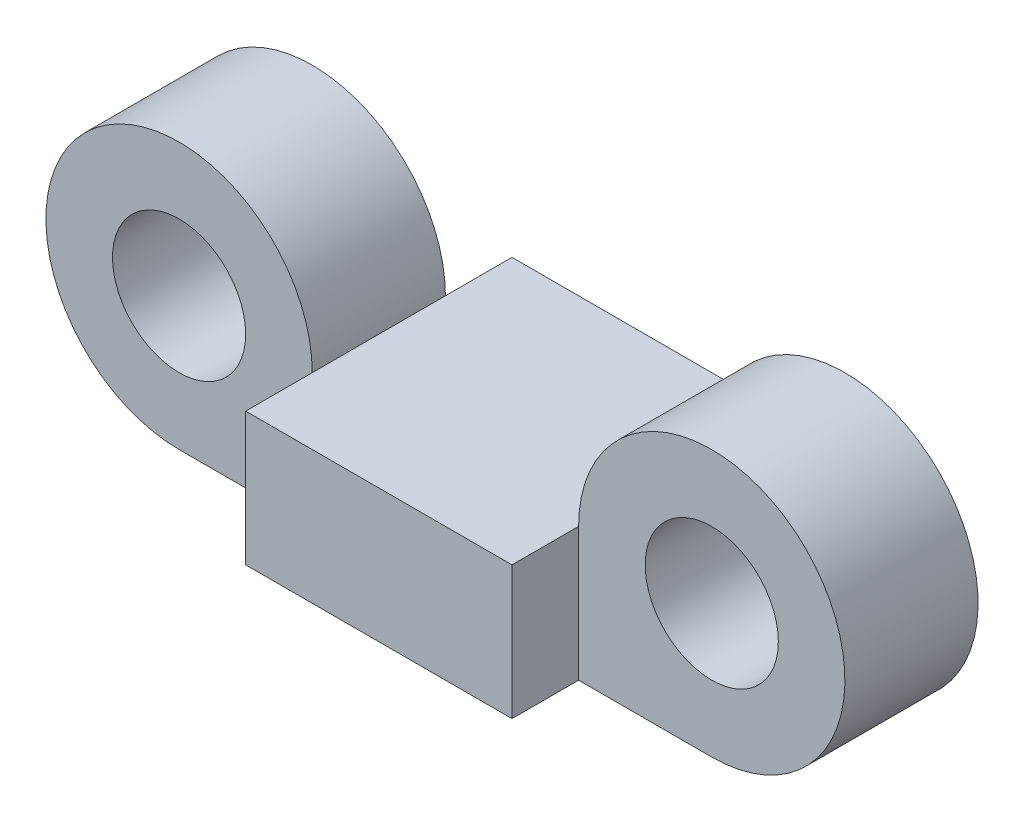
SolidWorks part; units mm, degrees
ref_plane "前视基准面" through (0, 0, 0) normal (0, 0, 1) x (1, 0, 0)
ref_plane "上视基准面" through (0, 0, 0) normal (0, 1, 0) x (1, 0, 0)
ref_plane "右视基准面" through (0, 0, 0) normal (1, 0, 0) x (0, 0, -1)
other "Configuration Table"
sketch "Sketch1" plane through (0, 0, 0) normal (0, 0, 1) x (1, 0, 0)
  line L0 (0, 0) -> (20, 0) construction
  line L1 (10, 0) -> (10, 3.3087) construction
  line L2 (0, -5) -> (20, -5)
  line L3 (20, -5) -> (20, 0)
  line L4 (20, 0) -> (0, 0)
  circle A0 centre (0, 0) radius 2.5
  circle A1 centre (0, 0) radius 5
  circle A4 centre (20, 0) radius 2.5
  circle A5 centre (20, 0) radius 5
  dimension "D1" = 5
  dimension "10" = 10
  dimension "D3" = 20
extrude "Boss-Extrude1" add sketch "Sketch1" along normal blind 5
sketch "Sketch2" plane through (0, 0, 0) normal (0, 1, 0) x (1, 0, 0)
  line L0 (10, 0) -> (10, -5) construction
  line L1 (15, 0) -> (5, 0) construction
  line L2 (15, -5) -> (5, -5) construction
  line L3 (10, -5) -> (10, -2.5) construction
  line L5 (5, -7.5) -> (15, -7.5)
  line L6 (5, -7.5) -> (5, 2.5)
  line L7 (5, 2.5) -> (15, 2.5)
  line L8 (15, -7.5) -> (15, 2.5)
  line L9 (5, -7.5) -> (15, 2.5) construction
  line L10 (5, 2.5) -> (15, -7.5) construction
  dimension "D1" = 10
  dimension "D2" = 10
extrude "Boss-Extrude2" add sketch "Sketch2" against normal blind 5
